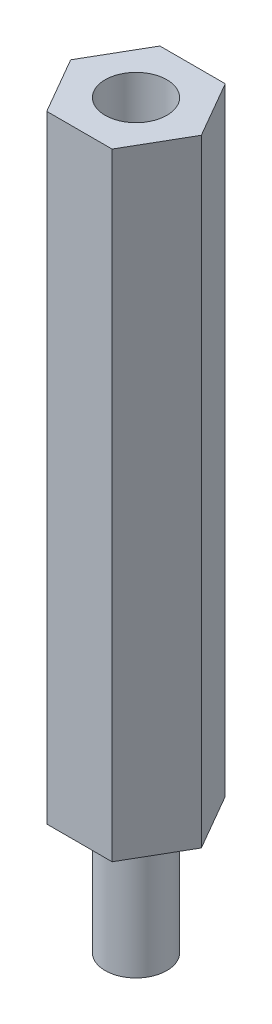
SolidWorks part; units mm, degrees
ref_plane "Front Plane" through (0, 0, 0) normal (0, 0, 1) x (1, 0, 0)
ref_plane "Top Plane" through (0, 0, 0) normal (0, 1, 0) x (1, 0, 0)
ref_plane "Right Plane" through (0, 0, 0) normal (1, 0, 0) x (0, 0, -1)
sketch "Sketch1" plane through (0, 0, 0) normal (0, 1, 0) x (1, 0, 0)
  line L0 (0, 0) -> (-3.1754, 0) construction
  line L1 (-1.5877, -2.75) -> (1.5877, -2.75)
  line L2 (1.5877, -2.75) -> (3.1754, 0)
  line L3 (3.1754, 0) -> (1.5877, 2.75)
  line L4 (1.5877, 2.75) -> (-1.5877, 2.75)
  line L5 (-1.5877, 2.75) -> (-3.1754, 0)
  line L6 (-3.1754, 0) -> (-1.5877, -2.75)
  circle A0 centre (0, 0) radius 2.75 construction
  dimension "D1" = 5.5
extrude "Boss-Extrude1" add sketch "Sketch1" along normal blind 30
sketch "Sketch2" plane through (0, 30, 0) normal (0, 1, 0) x (1, 0, 0)
  circle A0 centre (0, 0) radius 1.5
  dimension "D1" = 3
extrude "Cut-Extrude1" cut sketch "Sketch2" against normal blind 15
sketch "Sketch3" plane through (0, 0, 0) normal (0, -1, 0) x (1, 0, 0)
  circle A0 centre (0, 0) radius 1.5
  dimension "D1" = 3
extrude "Boss-Extrude2" add sketch "Sketch3" along normal blind 6
